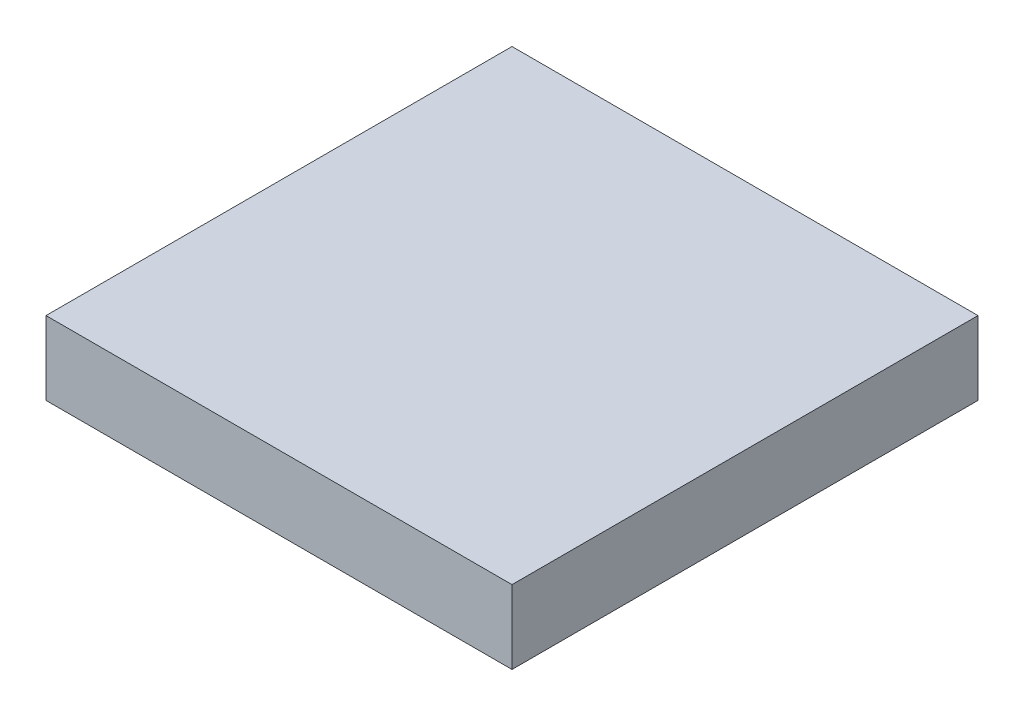
SolidWorks part; units mm, degrees
ref_plane "Front" through (0, 0, 0) normal (0, 0, 1) x (1, 0, 0)
ref_plane "Top" through (0, 0, 0) normal (0, 1, 0) x (1, 0, 0)
ref_plane "Right" through (0, 0, 0) normal (1, 0, 0) x (0, 0, -1)
sketch "Sketch1" plane through (0, 0, 0) normal (0, 1, 0) x (1, 0, 0)
  line L1 (-14.9, -14.9) -> (14.9, -14.9)
  line L2 (-14.9, -14.9) -> (-14.9, 14.9)
  line L3 (-14.9, 14.9) -> (14.9, 14.9)
  line L4 (14.9, -14.9) -> (14.9, 14.9)
  line L5 (-14.9, -14.9) -> (14.9, 14.9) construction
  line L6 (-14.9, 14.9) -> (14.9, -14.9) construction
  point P0 (0, 0)
  dimension "D1" = 29.8
extrude "Boss-Extrude1" add sketch "Sketch1" along normal blind 4.7
